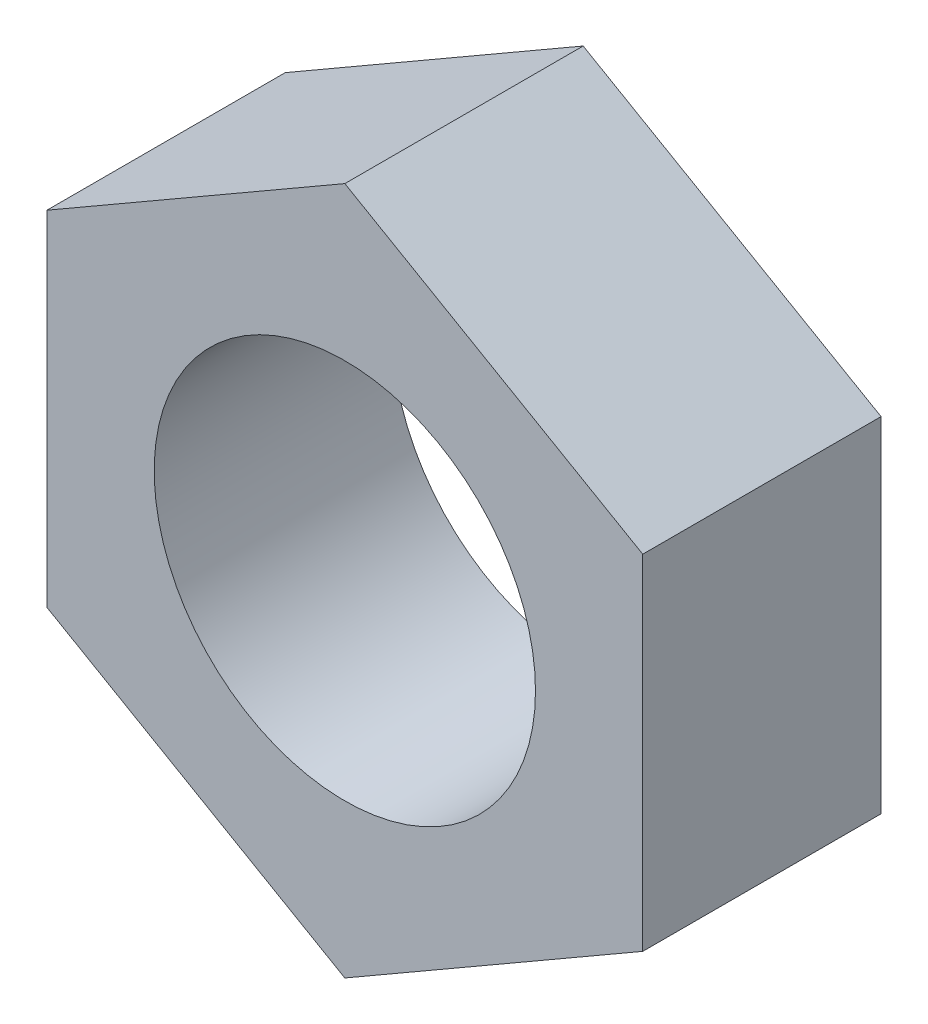
SolidWorks part; units mm, degrees
ref_plane "Front Plane" through (0, 0, 0) normal (0, 0, 1) x (1, 0, 0)
ref_plane "Top Plane" through (0, 0, 0) normal (0, 1, 0) x (1, 0, 0)
ref_plane "Right Plane" through (0, 0, 0) normal (1, 0, 0) x (0, 0, -1)
sketch "Sketch1" plane through (0, 0, 0) normal (0, 0, 1) x (1, 0, 0)
  line L0 (0, -6.8741) -> (0, 6.8741)
  line L1 (0, 6.8741) -> (11.9063, 13.7482)
  line L2 (11.9063, 13.7482) -> (23.8125, 6.8741)
  line L3 (23.8125, 6.8741) -> (23.8125, -6.8741)
  line L4 (23.8125, -6.8741) -> (11.9063, -13.7482)
  line L5 (11.9063, -13.7482) -> (0, -6.8741)
  point P7 (0, 0)
  point P8 (0, 0)
  point P9 (0, 0)
  point P10 (0, 0)
  dimension "D1" = 23.8125
  dimension "D2" = 120
extrude "Boss-Extrude1" add sketch "Sketch1" along normal mid plane 9.525
sketch "Sketch2" plane through (0, 0, 4.7625) normal (0, 0, 1) x (1, 0, 0)
  line L0 (0, 6.8741) -> (0, -6.8741) construction
  circle A0 centre (11.9063, 0) radius 7.62
  point P4 (0, 0)
  dimension "D2" = 15.24
  dimension "D1" = 11.9062
extrude "Cut-Extrude1" cut sketch "Sketch2" against normal through all
